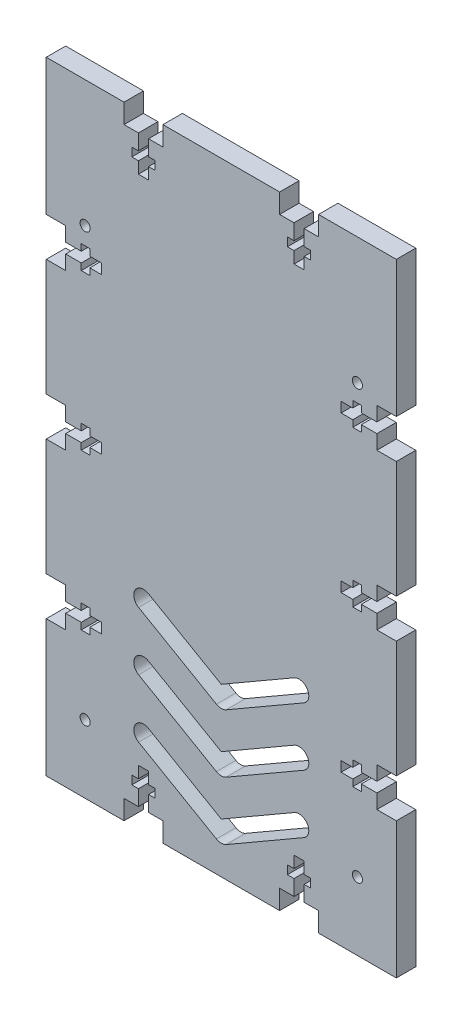
SolidWorks part; units mm, degrees
ref_plane "Front Plane" through (0, 0, 0) normal (0, 0, 1) x (1, 0, 0)
ref_plane "Top Plane" through (0, 0, 0) normal (0, 1, 0) x (1, 0, 0)
ref_plane "Right Plane" through (0, 0, 0) normal (1, 0, 0) x (0, 0, -1)
sketch "Sketch1" plane through (0, 0, 0) normal (0, 0, 1) x (1, 0, 0)
  line L1 (57.15, -101.6) -> (-57.15, -101.6)
  line L2 (57.15, -101.6) -> (57.15, 101.6)
  line L3 (57.15, 101.6) -> (-57.15, 101.6)
  line L4 (-57.15, -101.6) -> (-57.15, 101.6)
  line L5 (57.15, -101.6) -> (-57.15, 101.6) construction
  line L6 (57.15, 101.6) -> (-57.15, -101.6) construction
  point P0 (0, 0)
  dimension "D1" = 114.3
  dimension "D2" = 203.2
extrude "Boss-Extrude1" add sketch "Sketch1" along normal blind 6.35
sketch "Sketch2" plane through (0, 0, 6.35) normal (0, 0, 1) x (1, 0, 0)
  line L0 (-57.15, 6.35) -> (-57.15, -6.35)
  line L1 (-57.15, 6.35) -> (-50.8, 6.35)
  line L2 (-57.15, 101.6) -> (-57.15, -101.6) construction
  line L3 (-50.8, 6.35) -> (-50.8, 1.651)
  line L4 (-50.8, 1.651) -> (-45.72, 1.651)
  line L5 (0, 0) -> (0, 101.6) construction
  line L6 (-45.72, 1.651) -> (-45.72, 3.81)
  line L7 (-45.72, 3.81) -> (-42.926, 3.81)
  line L8 (-42.926, 3.81) -> (-42.926, 1.651)
  line L9 (-42.926, 1.651) -> (-39.116, 1.651)
  line L10 (-39.116, 1.651) -> (-39.116, -1.651)
  line L11 (-39.116, -1.651) -> (-42.926, -1.651)
  line L12 (-42.926, -1.651) -> (-42.926, -3.81)
  line L13 (-42.926, -3.81) -> (-45.72, -3.81)
  line L14 (-45.72, -3.81) -> (-45.72, -1.651)
  line L15 (-45.72, -1.651) -> (-50.8, -1.651)
  line L16 (-50.8, -1.651) -> (-50.8, -6.35)
  line L17 (-50.8, -6.35) -> (-57.15, -6.35)
  line L18 (-39.116, 0) -> (0, 0) construction
  line L19 (57.15, 101.6) -> (-57.15, 101.6) construction
  dimension "D1" = 12.7
  dimension "D2" = 7.62
  dimension "D3" = 3.302
  dimension "D4" = 6.35
  dimension "D5" = 3.81
  dimension "D6" = 5.08
  dimension "D7" = 2.794
extrude "Cut-Extrude2" cut sketch "Sketch2" against normal through all
sketch "Sketch3" plane through (0, 0, 6.35) normal (0, 0, 1) x (1, 0, 0)
  line L0 (-31.75, 101.6) -> (-31.75, 95.25)
  line L1 (57.15, 101.6) -> (-57.15, 101.6) construction
  line L2 (-31.75, 95.25) -> (-27.051, 95.25)
  line L3 (-27.051, 95.25) -> (-27.051, 90.17)
  line L4 (-27.051, 90.17) -> (-29.21, 90.17)
  line L5 (-29.21, 90.17) -> (-29.21, 87.376)
  line L6 (-29.21, 87.376) -> (-27.051, 87.376)
  line L7 (-27.051, 87.376) -> (-27.051, 83.566)
  line L8 (-27.051, 83.566) -> (-23.749, 83.566)
  line L9 (-23.749, 83.566) -> (-23.749, 87.376)
  line L10 (-23.749, 87.376) -> (-21.59, 87.376)
  line L11 (-21.59, 87.376) -> (-21.59, 90.17)
  line L12 (-21.59, 90.17) -> (-23.749, 90.17)
  line L13 (-23.749, 90.17) -> (-23.749, 95.25)
  line L14 (-23.749, 95.25) -> (-19.05, 95.25)
  line L15 (-19.05, 95.25) -> (-19.05, 101.6)
  line L16 (-19.05, 101.6) -> (-31.75, 101.6)
  line L19 (-39.116, 1.651) -> (-39.116, -1.651) construction
  line L20 (-42.926, 3.81) -> (-42.926, 1.651) construction
  line L21 (-42.926, 1.651) -> (-39.116, 1.651) construction
  line L22 (-45.72, 3.81) -> (-42.926, 3.81) construction
  line L23 (-50.8, 1.651) -> (-45.72, 1.651) construction
  line L24 (-57.15, 6.35) -> (-50.8, 6.35) construction
  line L25 (-57.15, 6.35) -> (-57.15, -6.35) construction
  line L26 (-45.72, -3.81) -> (-45.72, -1.651) construction
  line L27 (-25.4, 83.566) -> (-25.4, 0) construction
  line L28 (-39.116, 0) -> (0, 0) construction
  line L29 (0, 0) -> (0, 101.6) construction
  dimension "D1" = 25.4
extrude "Cut-Extrude3" cut sketch "Sketch3" against normal through all
sketch "Sketch4" plane through (0, 0, 6.35) normal (0, 0, 1) x (1, 0, 0)
  line L0 (-57.15, 57.15) -> (-50.8, 57.15)
  line L1 (-57.15, 101.6) -> (-57.15, 6.35) construction
  line L2 (-50.8, 57.15) -> (-50.8, 52.451)
  line L3 (-50.8, 52.451) -> (-45.72, 52.451)
  line L4 (-45.72, 52.451) -> (-45.72, 54.61)
  line L5 (-45.72, 54.61) -> (-42.926, 54.61)
  line L6 (-42.926, 54.61) -> (-42.926, 52.451)
  line L7 (-42.926, 52.451) -> (-39.116, 52.451)
  line L8 (-39.116, 52.451) -> (-39.116, 49.149)
  line L9 (-39.116, 49.149) -> (-42.926, 49.149)
  line L10 (-42.926, 49.149) -> (-42.926, 46.99)
  line L11 (-42.926, 46.99) -> (-45.72, 46.99)
  line L12 (-45.72, 46.99) -> (-45.72, 49.149)
  line L13 (-45.72, 49.149) -> (-50.8, 49.149)
  line L14 (-50.8, 49.149) -> (-50.8, 44.45)
  line L15 (-50.8, 44.45) -> (-57.15, 44.45)
  line L16 (-57.15, 44.45) -> (-57.15, 57.15)
  line L17 (-57.15, 6.35) -> (-50.8, 6.35) construction
  line L18 (-50.8, 1.651) -> (-45.72, 1.651) construction
  line L19 (-45.72, 3.81) -> (-42.926, 3.81) construction
  line L20 (-42.926, 1.651) -> (-39.116, 1.651) construction
  line L21 (-39.116, 1.651) -> (-39.116, -1.651) construction
  line L22 (-42.926, 3.81) -> (-42.926, 1.651) construction
  line L24 (-45.72, 1.651) -> (-45.72, 3.81) construction
  line L25 (-50.8, 6.35) -> (-50.8, 1.651) construction
  line L26 (-39.116, 50.8) -> (0, 50.8) construction
  line L27 (0, 0) -> (0, 101.6) construction
  line L28 (-39.116, 0) -> (0, 0) construction
  dimension "D1" = 50.8
extrude "Cut-Extrude4" cut sketch "Sketch4" against normal through all
mirror "Mirror1" about plane through (0, 0, 0) normal (0, 1, 0) of "Cut-Extrude4", "Cut-Extrude3"
mirror "Mirror3" about plane through (0, 0, 0) normal (1, 0, 0) of "Cut-Extrude2", "Mirror1", "Cut-Extrude3", "Cut-Extrude4"
sketch "Sketch7" plane through (0, 0, 0) normal (0, 0, -1) x (-1, 0, 0)
  circle A0 centre (-44.45, 60.325) radius 1.651 construction
  circle A1 centre (-44.45, 60.325) radius 1.651
  circle A2 centre (44.45, 60.325) radius 1.651 construction
  circle A3 centre (44.45, 60.325) radius 1.651
  circle A4 centre (44.45, -79.375) radius 1.651 construction
  circle A5 centre (44.45, -79.375) radius 1.651
  circle A6 centre (-44.45, -79.375) radius 1.651 construction
  circle A7 centre (-44.45, -79.375) radius 1.651
extrude "Cut-Extrude7" cut sketch "Sketch7" against normal through all
sketch "Sketch8" plane through (0, 0, 6.35) normal (0, 0, 1) x (1, 0, 0)
  line L0 (0, 0) -> (0, -101.6) construction
  line L1 (-19.05, -101.6) -> (19.05, -101.6) construction
  line L2 (25.4, -83.566) -> (25.4, 83.566) construction
  line L3 (27.051, -83.566) -> (23.749, -83.566) construction
  line L4 (27.051, 83.566) -> (23.749, 83.566) construction
  line L5 (-25.4, -83.566) -> (-25.4, 83.566) construction
  line L6 (-27.051, -83.566) -> (-23.749, -83.566) construction
  line L7 (-27.051, 83.566) -> (-23.749, 83.566) construction
  line L8 (0, 0) -> (25.4, 0) construction
  line L9 (0, 0) -> (-25.4, 0) construction
  line L10 (12.7, 0) -> (12.7, -101.6) construction
  line L11 (-12.7, 0) -> (-12.7, -101.6) construction
  line L12 (26.9875, -76.9849) -> (1.5875, -91.6496)
  line L13 (0, -85.2338) -> (23.8125, -71.4857)
  line L14 (0, -85.2338) -> (-23.8125, -71.4857)
  line L15 (25.4, -74.2353) -> (0, -88.9) construction
  line L16 (0, -88.9) -> (-25.4, -74.2353) construction
  line L17 (-26.9875, -76.9849) -> (-1.5875, -91.6496)
  arc A0 (1.5875, -91.6496) -> (-1.5875, -91.6496) centre (0, -88.9) cw
  arc A1 (23.8125, -71.4857) -> (26.9875, -76.9849) centre (25.4, -74.2353) cw
  arc A2 (-26.9875, -76.9849) -> (-23.8125, -71.4857) centre (-25.4, -74.2353) cw
  point P35 (0, -92.075)
  dimension "D2" = 3.175
  dimension "D1" = 12.7
  dimension "D3" = 120
extrude "Cut-Extrude8" cut sketch "Sketch8" against normal through all
pattern_linear "LPattern1" count 3 spacing 19.05 along (0, 1, 0) of "Cut-Extrude8"
